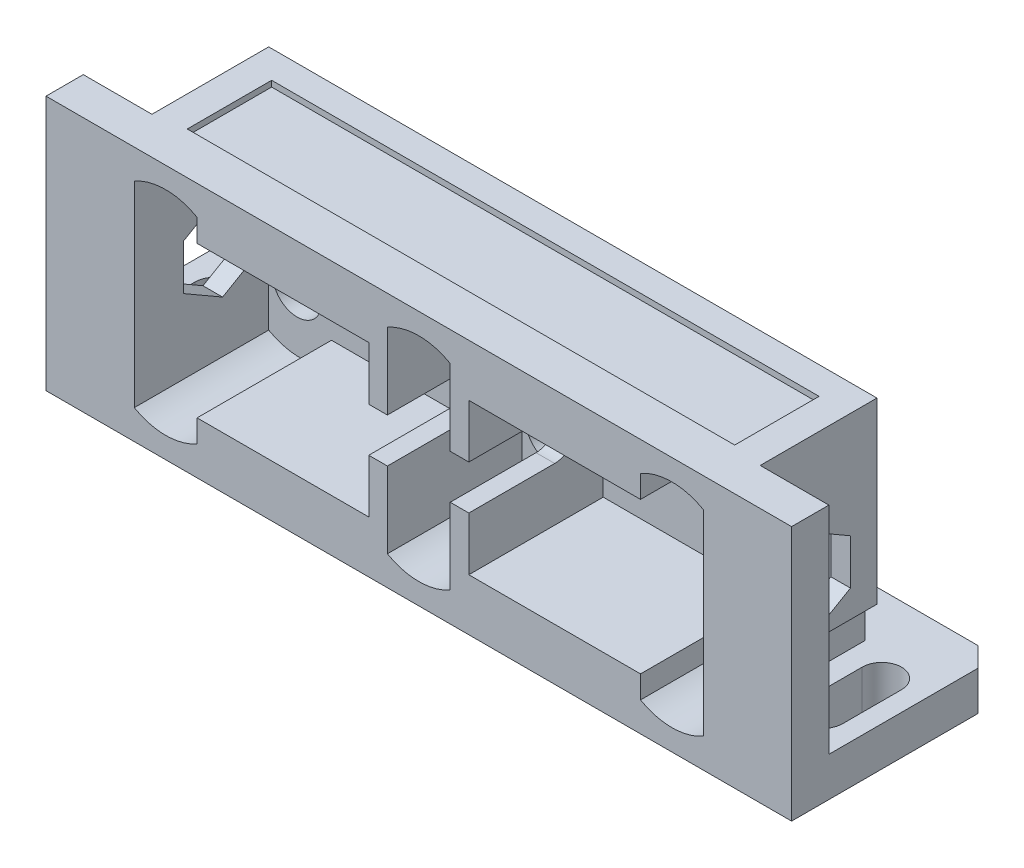
SolidWorks part; units mm, degrees
ref_plane "Front Plane" through (0, 0, 0) normal (0, 0, 1) x (1, 0, 0)
ref_plane "Top Plane" through (0, 0, 0) normal (0, 1, 0) x (1, 0, 0)
ref_plane "Right Plane" through (0, 0, 0) normal (1, 0, 0) x (0, 0, -1)
sketch "Sketch1" plane through (0, 0, 0) normal (0, 1, 0) x (1, 0, 0)
  line L1 (38, 10.5) -> (-38, 10.5)
  line L2 (38, 10.5) -> (38, -10.5)
  line L3 (38, -10.5) -> (-38, -10.5)
  line L4 (-38, 10.5) -> (-38, -10.5)
  line L5 (38, 10.5) -> (-38, -10.5) construction
  line L6 (38, -10.5) -> (-38, 10.5) construction
  point P0 (0, 0)
  dimension "D1" = 76
  dimension "D2" = 21
extrude "Boss-Extrude1" add sketch "Sketch1" along normal blind 4
sketch "Sketch2" plane through (0, 0, 0) normal (0, 1, 0) x (1, 0, 0)
  line L0 (-38, 10.5) -> (-38, -10.5) construction
  line L1 (-38, -6.7) -> (38, -6.7)
  line L2 (-38, -6.7) -> (-38, -10.5)
  line L3 (-38, -10.5) -> (38, -10.5)
  line L4 (38, -6.7) -> (38, -10.5)
  dimension "D1" = 3.8
extrude "Boss-Extrude2" add sketch "Sketch2" along normal blind 26
sketch "Sketch3" plane through (0, 0, 10.5) normal (0, 0, -1) x (-1, 0, 0)
  line L0 (-38, 26) -> (38, 26) construction
  line L1 (-31, 26) -> (31, 26)
  line L2 (-31, 26) -> (-31, 4)
  line L3 (-31, 4) -> (31, 4)
  line L4 (31, 26) -> (31, 4)
  line L5 (-38, 4) -> (38, 4) construction
  line L6 (0, 4) -> (0, 0) construction
  line L7 (-38, 0) -> (38, 0) construction
  dimension "D1" = 62
extrude "Boss-Extrude3" add sketch "Sketch3" along normal blind 15.7
chamfer "Chamfer2" distance 2 angle 45 2 edges at (-38, 2, -10.5) (38, 2, -10.5)
sketch "Sketch4" plane through (0, 26, 0) normal (0, 1, 0) x (1, 0, 0)
  line L3 (31, 5.2) -> (-31, 5.2) construction
  line L4 (-27.9, 2.4) -> (27.9, 2.4)
  line L5 (-27.9, 2.4) -> (-27.9, -6.2)
  line L6 (-27.9, -6.2) -> (27.9, -6.2)
  line L7 (27.9, 2.4) -> (27.9, -6.2)
  line L8 (31, 5.2) -> (31, -6.7) construction
  line L9 (0, 0) -> (0, -6.2) construction
  line L10 (-38, -10.5) -> (38, -10.5) construction
  dimension "D1" = 2.8
  dimension "D2" = 3.1
  dimension "D3" = 4.3
extrude "Cut-Extrude1" cut sketch "Sketch4" against normal blind 0.6
sketch "Sketch5" plane through (0, 4, 0) normal (0, 1, 0) x (1, 0, 0)
  line L0 (-34, 2.7) -> (-34, -3.3) construction
  line L1 (-32, 2.7) -> (-32, -3.3)
  line L2 (-36, 2.7) -> (-36, -3.3)
  line L3 (0, 0) -> (0, 10.5) construction
  line L4 (36, 10.5) -> (-36, 10.5) construction
  line L5 (34, 2.7) -> (34, -3.3) construction
  line L6 (32, 2.7) -> (32, -3.3)
  line L7 (36, 2.7) -> (36, -3.3)
  line L8 (-38, 8.5) -> (-38, -6.7) construction
  arc A0 (-32, 2.7) -> (-36, 2.7) centre (-34, 2.7) ccw
  arc A1 (-36, -3.3) -> (-32, -3.3) centre (-34, -3.3) ccw
  arc A2 (32, 2.7) -> (36, 2.7) centre (34, 2.7) cw
  arc A3 (36, -3.3) -> (32, -3.3) centre (34, -3.3) cw
  point P2 (-34, -0.3)
  point P14 (34, -0.3)
  point P19 (-34, 4.7)
  dimension "D1" = 4
  dimension "D2" = 8
  dimension "D3" = 5.8
  dimension "D4" = 2
extrude "Cut-Extrude2" cut sketch "Sketch5" against normal through all
sketch "Sketch6" plane through (0, 0, -10.5) normal (0, 0, -1) x (-1, 0, 0)
  line L0 (0, 0) -> (0, 26) construction
  line L1 (-16.75, 1.1) -> (-8.75, 1.1)
  line L2 (-16.75, 1.1) -> (-16.75, 5.1)
  line L3 (-16.75, 5.1) -> (-8.75, 5.1)
  line L4 (-8.75, 1.1) -> (-8.75, 5.1)
  line L5 (31, 26) -> (-31, 26) construction
  line L6 (8.75, 1.1) -> (8.75, 5.1)
  line L7 (16.75, 5.1) -> (8.75, 5.1)
  line L8 (16.75, 1.1) -> (16.75, 5.1)
  line L9 (16.75, 1.1) -> (8.75, 1.1)
  line L10 (-36, 0) -> (36, 0) construction
  dimension "D1" = 8
  dimension "D2" = 4
  dimension "D3" = 1.1
  dimension "D4" = 17.5
extrude "Cut-Extrude3" cut sketch "Sketch6" against normal blind 19.7
sketch "Sketch7" plane through (0, 0, 10.5) normal (0, 0, 1) x (1, 0, 0)
  line L0 (-38, 13) -> (0, 13) construction
  line L1 (29, 5.3) -> (-29, 5.3)
  line L2 (29, 5.3) -> (29, 20.7)
  line L3 (29, 20.7) -> (-29, 20.7)
  line L4 (-29, 5.3) -> (-29, 20.7)
  line L5 (29, 5.3) -> (-29, 20.7) construction
  line L6 (29, 20.7) -> (-29, 5.3) construction
  line L7 (-38, 26) -> (-38, 0) construction
  point P0 (0, 13)
  dimension "D1" = 58
  dimension "D2" = 15.4
extrude "Cut-Extrude4" cut sketch "Sketch7" against normal blind 13.7
sketch "Sketch8" plane through (0, 0, 10.5) normal (0, 0, 1) x (1, 0, 0)
  line L0 (-29, 20.7) -> (-29, 5.3) construction
  line L9 (-29, 20.7) -> (-29, 5.3) construction
  line L10 (-29, 23) -> (-22.6, 23) construction
  line L11 (-38, 13) -> (-29, 13) construction
  line L12 (-29, 23) -> (-29, 3)
  line L13 (-29, 3) -> (-22.6, 3) construction
  line L14 (-22.6, 23) -> (-22.6, 3)
  line L16 (-38, 26) -> (-38, 0) construction
  arc A0 (-29, 23) -> (-22.6, 23) centre (-25.8, 17.4015) cw
  arc A1 (-29, 3) -> (-22.6, 3) centre (-25.8, 8.5985) ccw
  point P9 (-25.8, 23.85)
  point P11 (-25.8, 2.15)
  dimension "D2" = 21.7
  dimension "D1" = 6.4
  dimension "D3" = 20
extrude "Cut-Extrude5" cut sketch "Sketch8" against normal up to surface (13.7 mm away) up to face at (0, 13, -3.2)
pattern_linear "LPattern1" count 3 spacing 25.8 along (1, 0, 0) of "Cut-Extrude5"
sketch "Sketch9" plane through (0, 0, 10.5) normal (0, 0, 1) x (1, 0, 0)
  line L0 (-22.6, 5.3) -> (-3.2, 5.3) construction
  line L6 (-3.2, 20.7) -> (-5.1, 20.7)
  line L20 (-3.2, 20.7) -> (-3.2, 5.3)
  line L21 (-3.2, 5.3) -> (-5.1, 5.3)
  line L22 (-5.1, 20.7) -> (-5.1, 5.3)
  line L23 (0, 0) -> (0, 26) construction
  line L24 (-38, 26) -> (38, 26) construction
  line L25 (5.1, 20.7) -> (5.1, 5.3)
  line L26 (3.2, 5.3) -> (5.1, 5.3)
  line L27 (3.2, 20.7) -> (3.2, 5.3)
  line L28 (3.2, 20.7) -> (5.1, 20.7)
  dimension "D1" = 1.9
extrude "Boss-Extrude4" add sketch "Sketch9" against normal up to next
sketch "Sketch10" plane through (-5.1, 0, 0) normal (-1, 0, 0) x (0, 0, 1)
  line L0 (10.5, 20.7) -> (10.5, 5.3) construction
  line L1 (10.5, 15.25) -> (1.75, 15.25)
  line L2 (10.5, 15.25) -> (10.5, 10.75)
  line L3 (10.5, 10.75) -> (1.75, 10.75)
  line L4 (1.75, 15.25) -> (1.75, 10.75) construction
  line L5 (-3.2, 13) -> (1.75, 13) construction
  line L6 (-3.2, 5.3) -> (-3.2, 20.7) construction
  arc A0 (1.75, 15.25) -> (1.75, 10.75) centre (1.75, 13) ccw
  point P11 (-0.5, 13)
  dimension "D1" = 4.5
  dimension "D2" = 11
extrude "Cut-Extrude6" cut sketch "Sketch10" against normal up to surface (10.2 mm away) up to face at (5.1, 13, 3.65)
sketch "Sketch11" plane through (-31, 0, 0) normal (-1, 0, 0) x (0, 0, 1)
  line L0 (1.5, 12.8812) -> (1.5, 17.5) construction
  line L1 (1.5, 17.5) -> (-2.5, 15.1906)
  line L2 (-2.5, 15.1906) -> (-2.5, 10.5718)
  line L3 (-2.5, 10.5718) -> (1.5, 8.2624)
  line L4 (1.5, 8.2624) -> (5.5, 10.5718)
  line L5 (5.5, 10.5718) -> (5.5, 15.1906)
  line L6 (5.5, 15.1906) -> (1.5, 17.5)
  line L7 (-5.2, 26) -> (6.7, 26) construction
  line L8 (-5.2, 4) -> (-5.2, 26) construction
  circle A0 centre (1.5, 12.8812) radius 4 construction
  dimension "D1" = 8
  dimension "D2" = 9.2376
  dimension "D3" = 8.5
  dimension "D4" = 2.7
extrude "Cut-Extrude7" cut sketch "Sketch11" against normal up to next
mirror "Mirror1" about plane through (0, 0, 0) normal (1, 0, 0) of "Cut-Extrude7"
sketch "Sketch12" plane through (0, 0, -5.2) normal (0, 0, -1) x (-1, 0, 0)
  line L0 (0, 0) -> (0, 26) construction
  line L1 (-31, 4) -> (-29.8, 4)
  line L2 (-31, 4) -> (-31, 7.8)
  line L3 (-31, 7.8) -> (-29.8, 7.8)
  line L4 (-29.8, 4) -> (-29.8, 7.8)
  line L5 (31, 26) -> (-31, 26) construction
  line L6 (29.8, 4) -> (29.8, 7.8)
  line L7 (31, 7.8) -> (29.8, 7.8)
  line L8 (31, 4) -> (31, 7.8)
  line L9 (31, 4) -> (29.8, 4)
  dimension "D1" = 3.8
  dimension "D2" = 1.2
extrude "Cut-Extrude8" cut sketch "Sketch12" against normal up to surface (11.9 mm away) up to face at (34.5, 15, 6.7)
sketch "Sketch13" plane through (0, 0, -5.2) normal (0, 0, -1) x (-1, 0, 0)
  line L1 (-31, 26) -> (-31, 7.8) construction
  line L2 (31, 26) -> (-31, 26) construction
  line L3 (-25.5, 18.1) -> (0.3, 18.1) construction
  line L4 (-25.5, 18.1) -> (-25.5, 8.1) construction
  circle A0 centre (-25.5, 18.1) radius 2.5
  circle A1 centre (0.3, 18.1) radius 2.5
  circle A2 centre (26.1, 18.1) radius 2.5
  circle A3 centre (0.3, 8.1) radius 2.5
  circle A4 centre (26.1, 8.1) radius 2.5
  circle A5 centre (-25.5, 8.1) radius 2.5
  dimension "D1" = 5
  dimension "D2" = 3
  dimension "D3" = 5.4
  dimension "D6" = 25.8
  dimension "D7" = 10
  dimension "D4" = 3
  dimension "D5" = 2
extrude "Cut-Extrude9" cut sketch "Sketch13" against normal up to next
